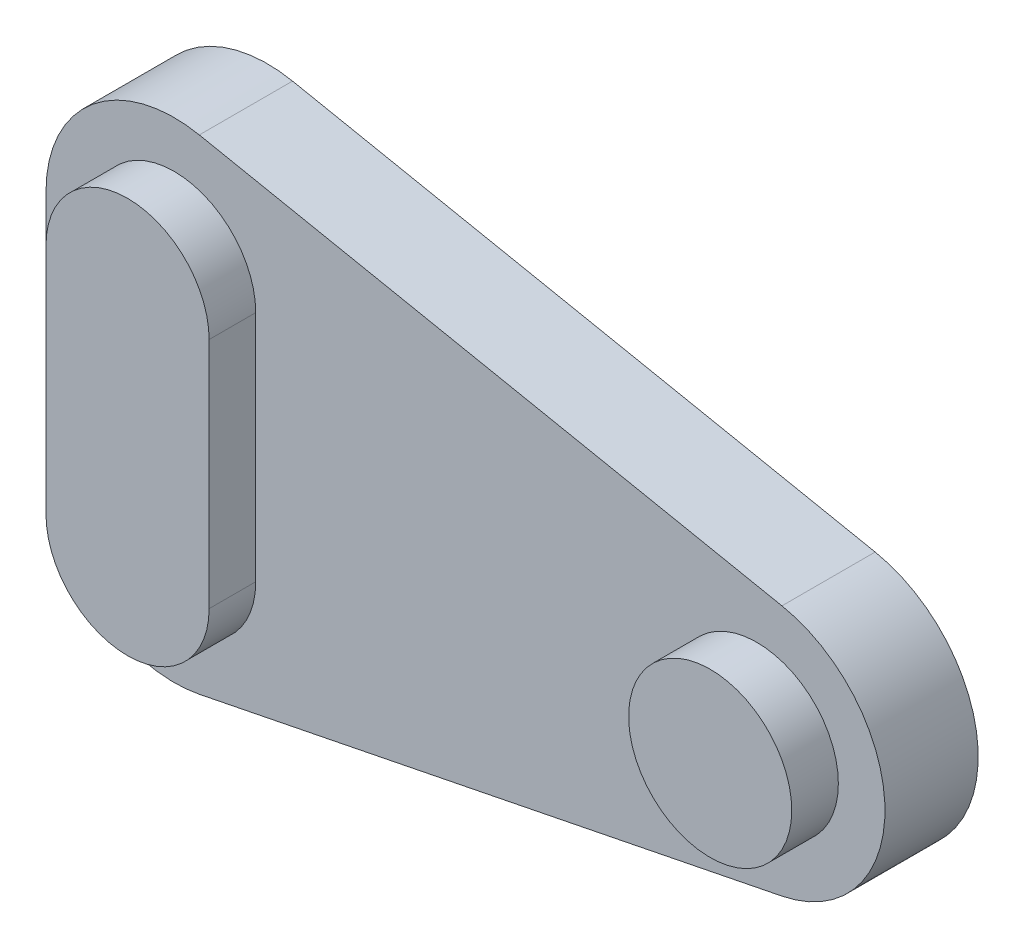
SolidWorks part; units mm, degrees
ref_plane "Front Plane" through (0, 0, 0) normal (0, 0, 1) x (1, 0, 0)
ref_plane "Top Plane" through (0, 0, 0) normal (0, 1, 0) x (1, 0, 0)
ref_plane "Right Plane" through (0, 0, 0) normal (1, 0, 0) x (0, 0, -1)
sketch "Sketch1" plane through (0, 0, 0) normal (0, 0, 1) x (1, 0, 0)
  line L0 (0, 0) -> (0, 12.7)
  line L1 (0, 6.35) -> (38.735, 6.35) construction
  line L2 (6.985, 0) -> (6.985, 12.7) construction
  line L3 (8.3549, 19.5494) -> (40.1049, 13.1994)
  line L4 (40.1049, -0.4994) -> (8.3549, -6.8494)
  arc A1 (40.1049, 13.1994) -> (40.1049, -0.4994) centre (38.735, 6.35) cw
  arc A2 (8.3549, -6.8494) -> (0, 0) centre (6.985, 0) cw
  arc A4 (8.3549, 19.5494) -> (0, 12.7) centre (6.985, 12.7) ccw
  point P12 (45.72, 6.35)
  point P13 (2.5566, 18.1018)
  point P18 (2.5566, -5.4018)
  dimension "D3" = 6.985
  dimension "D1" = 6.985
  dimension "D2" = 6.985
  dimension "D4" = 12.7
  dimension "D5" = 31.75
extrude "Boss-Extrude3" add sketch "Sketch1" along normal blind 5.08
sketch "Sketch6" plane through (0, 0, 5.08) normal (0, 0, 1) x (1, 0, 0)
  line L0 (11.43, 0) -> (2.54, 0)
  line L1 (2.54, 12.7) -> (2.54, 0)
  line L2 (11.43, 12.7) -> (2.54, 12.7)
  line L3 (11.43, 12.7) -> (11.43, 0)
  line L4 (2.54, 12.7) -> (6.985, 12.7)
  line L5 (2.54, 12.7) -> (2.54, 0)
  line L6 (11.43, 12.7) -> (11.43, 0)
  line L8 (2.54, 12.7) -> (11.43, 12.7)
  line L9 (2.54, 12.7) -> (2.54, 0)
  line L10 (2.54, 0) -> (11.43, 0)
  line L11 (11.43, 12.7) -> (11.43, 0)
  arc A0 (2.54, 12.7) -> (11.43, 12.7) centre (6.985, 12.7) cw
  arc A1 (2.54, 0) -> (11.43, 0) centre (6.985, 0) ccw
  circle A2 centre (38.735, 6.35) radius 4.445
  point P4 (6.985, 0)
  point P10 (6.985, 12.7)
  dimension "D2" = 8.89
  dimension "D1" = 4.445
extrude "Boss-Extrude4" add sketch "Sketch6" along normal blind 2.54 contours A0 L2 | L9 L8 L11 L10 | A1 L0 | A2
